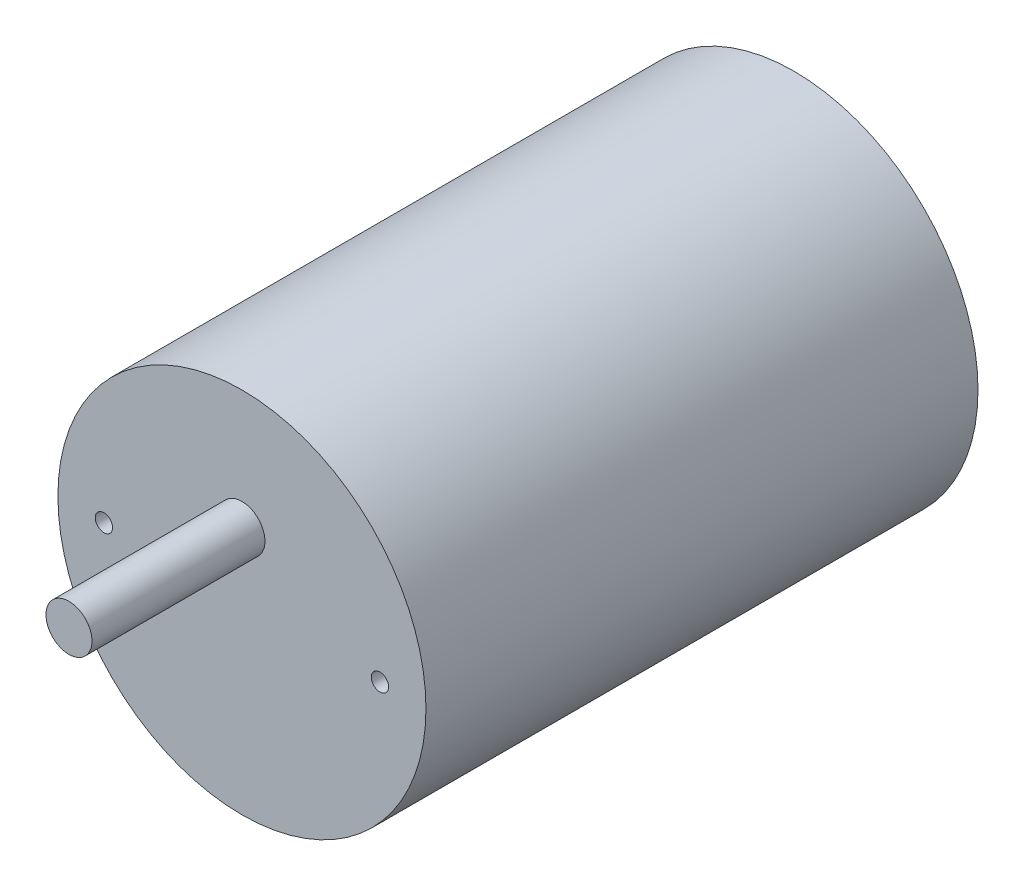
SolidWorks part; units mm, degrees
ref_plane "Front Plane" through (0, 0, 0) normal (0, 0, 1) x (1, 0, 0)
ref_plane "Top Plane" through (0, 0, 0) normal (0, 1, 0) x (1, 0, 0)
ref_plane "Right Plane" through (0, 0, 0) normal (1, 0, 0) x (0, 0, -1)
sketch "Sketch1" plane through (0, 0, 0) normal (0, 0, 1) x (1, 0, 0)
  circle A0 centre (0, 0) radius 25.4
extrude "Boss-Extrude1" add sketch "Sketch1" along normal blind 76.2
sketch "Sketch2" plane through (0, 0, 76.2) normal (0, 0, 1) x (1, 0, 0)
  circle A0 centre (0, 8.89) radius 3.175
extrude "Boss-Extrude2" add sketch "Sketch2" along normal blind 23.876
sketch "Sketch3" plane through (0, 0, 76.2) normal (0, 0, 1) x (1, 0, 0)
  circle A0 centre (19.05, 0) radius 1.1968
  circle A1 centre (-19.05, 0) radius 1.1968
extrude "Cut-Extrude1" cut sketch "Sketch3" against normal blind 2.54
